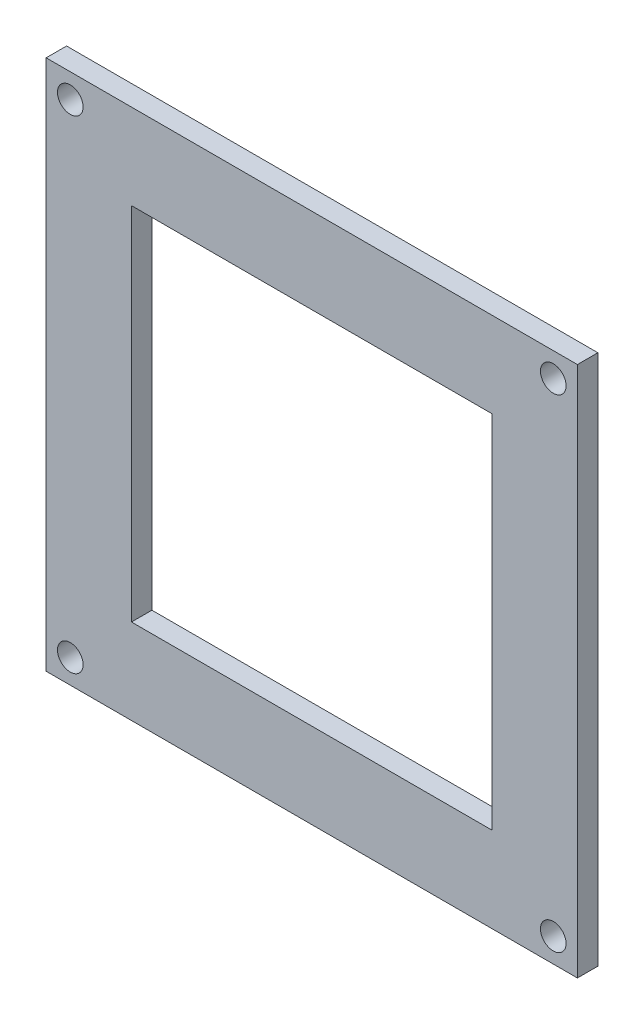
SolidWorks part; units mm, degrees
ref_plane "Front Plane" through (0, 0, 0) normal (0, 0, 1) x (1, 0, 0)
ref_plane "Top Plane" through (0, 0, 0) normal (0, 1, 0) x (1, 0, 0)
ref_plane "Right Plane" through (0, 0, 0) normal (1, 0, 0) x (0, 0, -1)
sketch "Sketch1" plane through (0, 0, 0) normal (0, 0, 1) x (1, 0, 0)
  line L1 (-30, 30) -> (30, 30) construction
  line L2 (-30, 30) -> (-30, -30) construction
  line L3 (-30, -30) -> (30, -30) construction
  line L4 (30, 30) -> (30, -30) construction
  line L5 (0, -30) -> (0, 30) construction
  line L6 (-30, 0) -> (30, 0) construction
  line L7 (-33, 33) -> (33, 33)
  line L8 (-33, 33) -> (-33, -33)
  line L9 (-33, -33) -> (33, -33)
  line L10 (33, 33) -> (33, -33)
  line L11 (0, -33) -> (0, 33) construction
  line L12 (-33, 0) -> (33, 0) construction
  line L13 (-22.4, 22.4) -> (22.4, 22.4)
  line L14 (-22.4, 22.4) -> (-22.4, -22.4)
  line L15 (-22.4, -22.4) -> (22.4, -22.4)
  line L16 (22.4, 22.4) -> (22.4, -22.4)
  line L17 (0, -22.4) -> (0, 22.4) construction
  line L18 (-22.4, 0) -> (22.4, 0) construction
  circle A0 centre (30, 30) radius 1.59
  circle A1 centre (-30, 30) radius 1.59
  circle A2 centre (-30, -30) radius 1.59
  circle A3 centre (30, -30) radius 1.59
  point P0 (0, 0)
  point P4 (0, 0)
  point P8 (0, 0)
  dimension "D2" = 3.18
  dimension "D1" = 60
  dimension "D3" = 44.8
  dimension "D4" = 66
extrude "Boss-Extrude1" add sketch "Sketch1" along normal blind 2.54
equation "\"D3@Sketch1\"=50.8 - 3*2"
